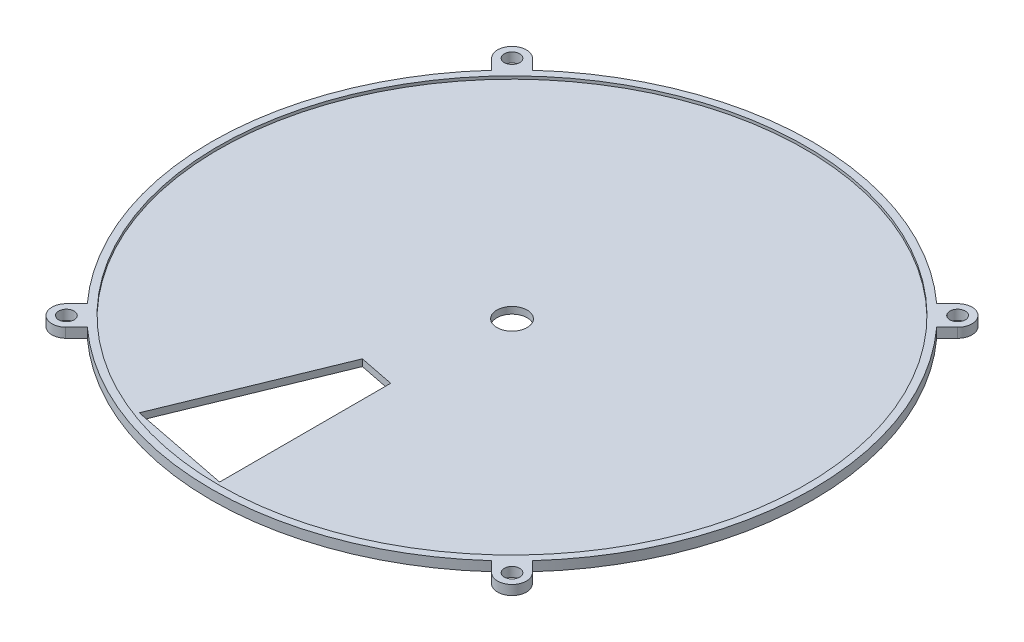
SolidWorks part; units mm, degrees
ref_plane "Спереди" through (0, 0, 0) normal (0, 0, 1) x (1, 0, 0)
ref_plane "Сверху" through (0, 0, 0) normal (0, 1, 0) x (1, 0, 0)
ref_plane "Справа" through (0, 0, 0) normal (1, 0, 0) x (0, 0, -1)
sketch "Эскиз1" plane through (0, 0, 0) normal (0, 1, 0) x (1, 0, 0)
  line L0 (0, 62.5) -> (0, -62.5) construction
  line L1 (0, -62.5) -> (-62.5, 0) construction
  line L2 (-62.5, 0) -> (62.5, 0) construction
  line L3 (0, 0) -> (-31.25, -31.25) construction
  line L4 (-31.25, -31.25) -> (-44.1942, -44.1942) construction
  line L5 (-44.1942, -44.1942) -> (-47.4469, -47.4469) construction
  line L6 (-48.5317, 44.2935) -> (-46.2624, 42.0242)
  line L7 (-44.1942, 48.4368) -> (-42.0219, 46.2646)
  line L8 (-44.1942, 44.1942) -> (-47.4469, 47.4469) construction
  line L9 (44.2935, 48.5317) -> (42.0242, 46.2624)
  line L10 (48.4368, 44.1942) -> (46.2646, 42.0219)
  line L11 (44.1942, 44.1942) -> (47.4469, 47.4469) construction
  line L12 (48.5317, -44.2935) -> (46.2624, -42.0242)
  line L13 (44.1942, -48.4368) -> (42.0219, -46.2646)
  line L14 (-44.2935, -48.5317) -> (-42.0242, -46.2624)
  line L15 (-48.4368, -44.1942) -> (-46.2646, -42.0219)
  line L16 (44.1942, -44.1942) -> (47.4469, -47.4469) construction
  arc A0 (46.2624, -42.0242) -> (46.2646, 42.0219) centre (0, 0) ccw
  circle A1 centre (-46.3155, -46.3155) radius 1.6
  arc A2 (-48.4368, -44.1942) -> (-44.0993, -48.3375) centre (-46.3155, -46.3155) ccw
  circle A3 centre (-46.3155, 46.3155) radius 1.6
  arc A4 (-44.1942, 48.4368) -> (-48.3375, 44.0993) centre (-46.3155, 46.3155) ccw
  circle A5 centre (46.3155, 46.3155) radius 1.6
  arc A6 (48.4368, 44.1942) -> (44.0993, 48.3375) centre (46.3155, 46.3155) ccw
  circle A7 centre (46.3155, -46.3155) radius 1.6
  arc A8 (44.1942, -48.4368) -> (48.3375, -44.0993) centre (46.3155, -46.3155) ccw
  arc A9 (42.0242, 46.2624) -> (-42.0219, 46.2646) centre (0, 0) ccw
  arc A10 (-46.2624, 42.0242) -> (-46.2646, -42.0219) centre (0, 0) ccw
  arc A11 (-42.0242, -46.2624) -> (42.0219, -46.2646) centre (0, 0) ccw
  point P5 (-46.3155, -46.3155)
  point P15 (-44.1942, -44.1942)
  point P17 (-46.3155, 46.3155)
  point P27 (-44.1942, 44.1942)
  point P33 (46.3155, 46.3155)
  point P38 (44.1942, 44.1942)
  point P44 (46.3155, -46.3155)
  point P49 (44.1942, -44.1942)
  point P55 (0, 0)
  dimension "D1" = 125
  dimension "D3" = 3.2
  dimension "D4" = 6
  dimension "D2" = 65.5
  dimension "D5" = 4
extrude "Бобышка-Вытянуть1" add sketch "Эскиз1" along normal blind 2 contours L14 A11 L13 A8 L12 A0 L10 A6 L9 A9 L7 A4 L6 A10 L15 A2 A1 A3 A5 A7
sketch "Эскиз2" plane through (0, 2, 0) normal (0, 1, 0) x (1, 0, 0)
  circle A1 centre (0, 0) radius 61
  dimension "D1" = 122
extrude "Вырез-Вытянуть3" cut sketch "Эскиз2" against normal blind 0.6
sketch "Эскиз3" plane through (0, 1.4, 0) normal (0, 1, 0) x (1, 0, 0)
  circle A0 centre (0, 0) radius 3.15
  dimension "D1" = 6.3
extrude "Вырез-Вытянуть4" cut sketch "Эскиз3" against normal blind 2
sketch "Эскиз6" plane through (0, 0, 0) normal (0, 1, 0) x (1, 0, 0)
  line L0 (0, 61) -> (0, -61) construction
  line L1 (0, -61) -> (0, -62.5) construction
  line L2 (-61, 0) -> (0, 0) construction
  line L3 (-43.1335, -43.1335) -> (0, 0) construction
  line L4 (-30.5, -30.5) -> (0, 0) construction
  line L5 (0, -61) -> (0, 0) construction
  line L6 (0, 0) -> (-43.1335, -43.1335) construction
  line L7 (0, 0) -> (-21.5668, -52.0668) construction
  line L8 (-21.5668, -52.0668) -> (-23.9177, -57.7425) construction
  line L9 (-23.9177, -57.7425) -> (-23.3437, -56.3567) construction
  line L10 (-21.4282, -52.1242) -> (-23.7791, -57.7999)
  line L11 (-0.15, -61) -> (-0.15, -62.5)
  line L12 (-0.15, -61) -> (0, -61)
  line L13 (-8.9548, -21.6188) -> (0, -23.4) construction
  line L14 (-23.205, -56.4139) -> (0, -61) construction
  line L15 (-23.1244, -56.2192) -> (-8.9548, -21.6188) construction
  line L16 (0, -23.4) -> (0, -61) construction
  line L17 (-21.8183, -55.6686) -> (-8.3417, -22.7603)
  line L18 (-8.3417, -22.7603) -> (-1, -24.2207)
  line L19 (-1, -24.2207) -> (-1, -59.783)
  line L20 (-23.0112, -55.4329) -> (-22.8148, -55.4717)
  line L21 (-21.8183, -55.6686) -> (-1, -59.783)
  line L22 (-22.199, -56.5982) -> (-8.3417, -22.7603) construction
  line L23 (0, -59.9807) -> (0.1939, -60.019)
  line L24 (-23.0112, -55.4329) -> (0.1939, -60.019) construction
  line L25 (-1, -60.8024) -> (-1, -61)
  line L27 (-1, -24.2207) -> (-1, -61) construction
  arc A0 (0, -61) -> (-23.205, -56.4139) centre (0, 0) ccw construction
  arc A1 (-0.15, -62.4998) -> (-23.7791, -57.7997) centre (0, 0) ccw construction
  circle A2 centre (0, 0) radius 23.4 construction
  point P19 (-8.9548, -21.6188)
  point P20 (0, -23.4)
  point P21 (-8.9548, -21.6188)
  point P24 (-23.1244, -56.2192)
  dimension "D1" = 122
  dimension "D2" = 125
  dimension "D5" = 46.8
  dimension "D3" = 0.15
  dimension "D4" = 0.15
  dimension "D6" = 1
  dimension "D7" = 1
extrude "Вырез-Вытянуть6" cut sketch "Эскиз6" against normal blind 58 and the other way blind 56 contours L21 L19 L18 L17
